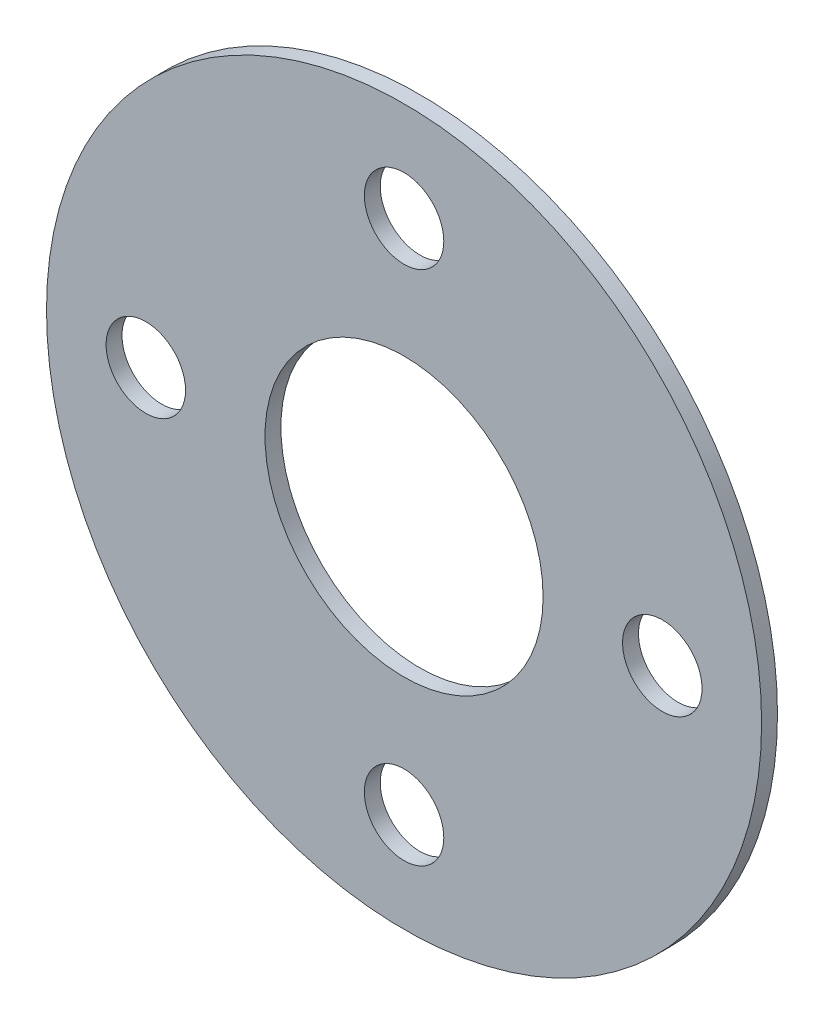
SolidWorks part; units mm, degrees
material "Plain Carbon Steel"
ref_plane "Front Plane" through (0, 0, 0) normal (0, 0, 1) x (1, 0, 0)
ref_plane "Top Plane" through (0, 0, 0) normal (0, 1, 0) x (1, 0, 0)
ref_plane "Right Plane" through (0, 0, 0) normal (1, 0, 0) x (0, 0, -1)
sketch "Sketch1" plane through (0, 0, 0) normal (0, 0, 1) x (1, 0, 0)
  circle A0 centre (0, 0) radius 45
  circle A1 centre (0, 0) radius 32.5 construction
  circle A2 centre (0, 32.5) radius 5
  circle A3 centre (32.5, 0) radius 5
  circle A4 centre (0, -32.5) radius 5
  circle A5 centre (-32.5, 0) radius 5
  point P15 (0, 0)
  dimension "D1" = 90
  dimension "D2" = 65
  dimension "D3" = 10
  dimension "D4" = 4
extrude "Boss-Extrude1" add sketch "Sketch1" along normal blind 2
sketch "Sketch2" plane through (0, 0, 2) normal (0, 0, 1) x (1, 0, 0)
  circle A0 centre (0, 0) radius 17.5
  dimension "D1" = 35
extrude "Cut-Extrude1" cut sketch "Sketch2" against normal blind 2
